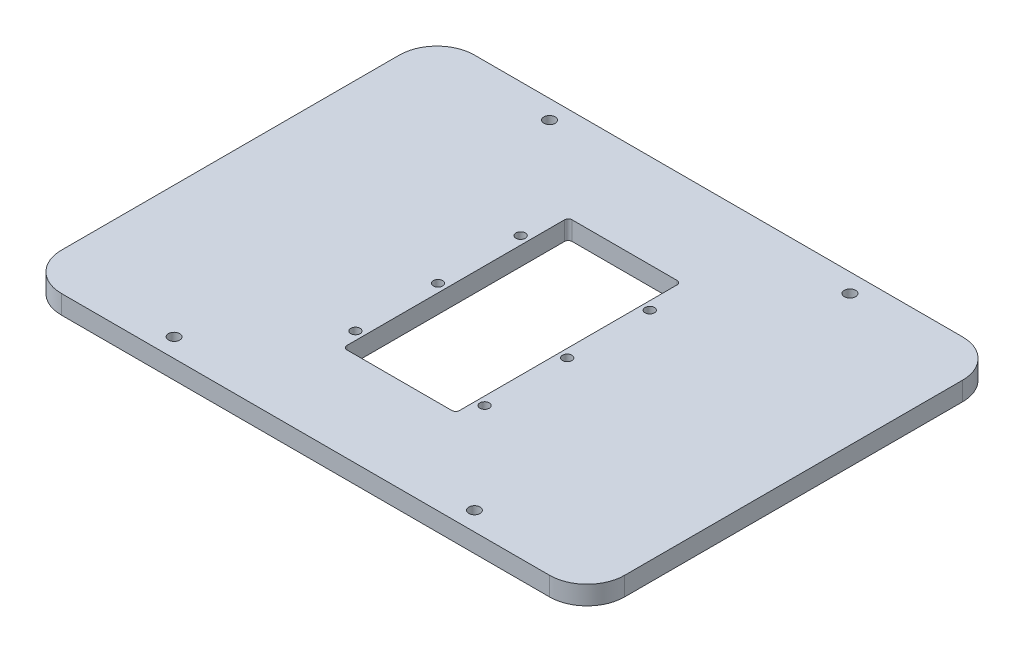
SolidWorks part; units mm, degrees
ref_plane "Plano frontal" through (0, 0, 0) normal (0, 0, 1) x (1, 0, 0)
ref_plane "Plano superior" through (0, 0, 0) normal (0, 1, 0) x (1, 0, 0)
ref_plane "Plano direito" through (0, 0, 0) normal (1, 0, 0) x (0, 0, -1)
sketch "Esboço1" plane through (0, 0, 0) normal (0, 1, 0) x (1, 0, 0)
  line L0 (-40, -50) -> (-40, -2.6613) construction
  line L1 (65, -55) -> (-65, -55)
  line L2 (75, -45) -> (75, 45)
  line L3 (65, 55) -> (-65, 55)
  line L4 (-75, -45) -> (-75, 45)
  line L5 (75, -55) -> (-75, 55) construction
  line L6 (75, 55) -> (-75, -55) construction
  line L7 (-40, -2.6613) -> (-75, -2.6613) construction
  line L8 (40, -50) -> (40, -2.6613) construction
  line L9 (40, -2.6613) -> (75, -2.6613) construction
  line L10 (-74.8866, 0) -> (99.4704, 0) construction
  line L11 (0, 30) -> (0, -30) construction
  line L12 (14, 30) -> (-14, 30)
  line L13 (15, 29) -> (15, -29)
  line L14 (14, -30) -> (-14, -30)
  line L15 (-15, 29) -> (-15, -29)
  line L16 (15, 30) -> (-15, -30) construction
  line L17 (15, -30) -> (-15, 30) construction
  arc A0 (65, -55) -> (75, -45) centre (65, -45) ccw
  arc A1 (-65, -55) -> (-75, -45) centre (-65, -45) cw
  arc A2 (-65, 55) -> (-75, 45) centre (-65, 45) ccw
  arc A3 (75, 45) -> (65, 55) centre (65, 45) ccw
  circle A4 centre (-40, -50) radius 1.5
  circle A5 centre (40, -50) radius 1.5
  circle A6 centre (40, 50) radius 1.5
  circle A7 centre (-40, 50) radius 1.5
  circle A8 centre (17.2, 19.5) radius 1.25
  circle A9 centre (17.2, -2.5) radius 1.25
  circle A10 centre (17.2, -24.5) radius 1.25
  arc A11 (15, -29) -> (14, -30) centre (14, -29) cw
  arc A12 (-14, -30) -> (-15, -29) centre (-14, -29) cw
  arc A13 (14, 30) -> (15, 29) centre (14, 29) cw
  arc A14 (-14, 30) -> (-15, 29) centre (-14, 29) ccw
  circle A15 centre (-17.2, -24.5) radius 1.25
  circle A16 centre (-17.2, -2.5) radius 1.25
  circle A17 centre (-17.2, 19.5) radius 1.25
  point P0 (0, 0)
  point P32 (0, 0)
  dimension "D3" = 10
  dimension "D4" = 3
  dimension "D5" = 3
  dimension "D6" = 80
  dimension "D8" = 60
  dimension "D10" = 2.5
  dimension "D13" = 2.5
  dimension "D16" = 2.5
  dimension "D17" = 1
  dimension "D1" = 110
  dimension "D2" = 150
  dimension "D7" = 5
  dimension "D9" = 30
  dimension "D11" = 10.5
  dimension "D12" = 22
  dimension "D14" = 2.2
  dimension "D15" = 22
extrude "Ressalto-extrusão1" add sketch "Esboço1" along normal blind 5
